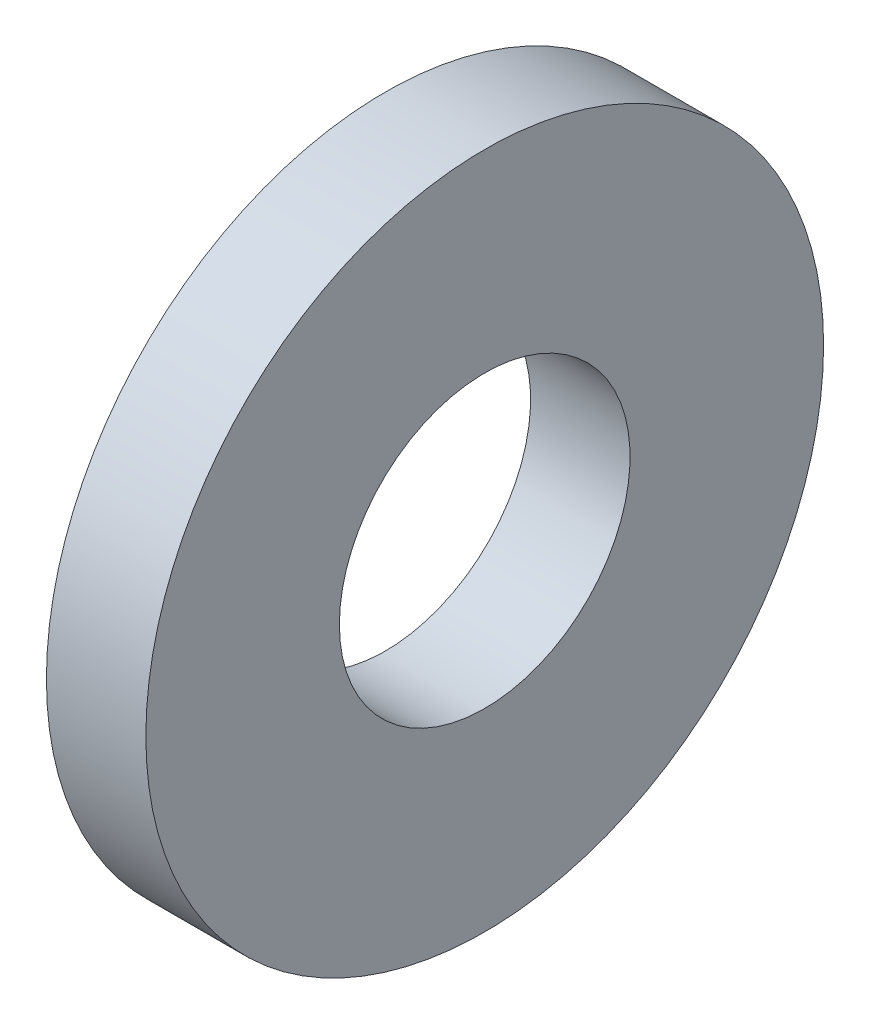
SolidWorks part; units mm, degrees
ref_plane "Front Plane" through (0, 0, 0) normal (0, 0, 1) x (1, 0, 0)
ref_plane "Top Plane" through (0, 0, 0) normal (0, 1, 0) x (1, 0, 0)
ref_plane "Right Plane" through (0, 0, 0) normal (1, 0, 0) x (0, 0, -1)
sketch "Sketch1" plane through (0, 0, 0) normal (1, 0, 0) x (0, 0, -1)
  circle A0 centre (0, 0) radius 5.6261
  circle A1 centre (0, 0) radius 2.413
  dimension "OD" = 11.2522
  dimension "ID" = 4.826
extrude "Boss-Extrude1" add sketch "Sketch1" along normal blind 1.651
